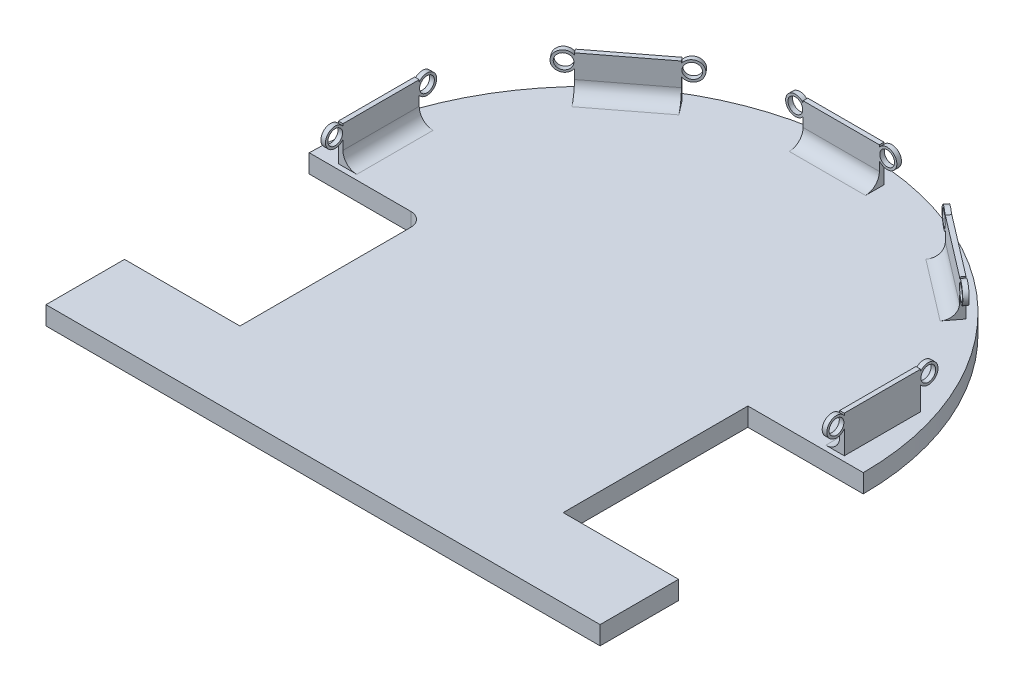
SolidWorks part; units mm, degrees
ref_plane "Front Plane" through (0, 0, 0) normal (0, 0, 1) x (1, 0, 0)
ref_plane "Top Plane" through (0, 0, 0) normal (0, 1, 0) x (1, 0, 0)
ref_plane "Right Plane" through (0, 0, 0) normal (1, 0, 0) x (0, 0, -1)
sketch "Sketch2" plane through (0, 0, 0) normal (0, 1, 0) x (1, 0, 0)
  line L0 (0, 0) -> (0, -17)
  line L1 (0, -17) -> (120, -17)
  line L2 (120, -17) -> (120, 0)
  line L3 (120, 0) -> (95, 0)
  line L4 (95, 0) -> (95, 40)
  line L5 (95, 40) -> (120, 40)
  line L6 (0, 0) -> (25, 0)
  line L7 (25, 0) -> (25, 40)
  line L8 (25, 40) -> (0, 40)
  arc A0 (0, 40) -> (120, 40) centre (60, 40) cw
  dimension "D1" = 120
  dimension "D2" = 25
  dimension "D3" = 25
  dimension "D4" = 25
  dimension "D5" = 25
  dimension "D6" = 40
  dimension "D7" = 40
  dimension "D15" = 17
extrude "Boss-Extrude1" add sketch "Sketch2" against normal blind 4
fillet "Fillet1" radius 3 1 edges at (25, -2, -40)
sketch "Sketch3" plane through (0, 0, 0) normal (0, 1, 0) x (1, 0, 0)
  line L0 (25, 37) -> (25, 0) construction
  line L1 (5.2129, 57.6133) -> (6.2129, 57.6133)
  line L2 (5.2129, 57.6133) -> (5.2129, 41.0933)
  line L3 (5.2129, 41.0933) -> (6.2129, 41.0933)
  line L4 (6.2129, 57.6133) -> (6.2129, 41.0933)
  line L5 (0, 40) -> (22, 40) construction
  dimension "D1" = 1
  dimension "D2" = 16.52
  dimension "D3" = 1.0933
  dimension "D4" = 18.7871
extrude "Boss-Extrude2" add sketch "Sketch3" along normal blind 8
sketch "Sketch4" plane through (5.2129, 0, 0) normal (-1, 0, 0) x (0, 0, 1)
  line L0 (-57.6133, 8) -> (-57.6133, 0) construction
  line L1 (-57.6133, 0) -> (-41.0933, 0) construction
  circle A0 centre (-59.2933, 6.3) radius 2.1
  dimension "D1" = 4.2
  dimension "D2" = 1.68
  dimension "D3" = 6.3
extrude "Boss-Extrude3" add sketch "Sketch4" against normal blind 1 contours A0
sketch "Sketch5" plane through (5.2129, 0, 0) normal (-1, 0, 0) x (0, 0, 1)
  circle A0 centre (-59.2933, 6.3) radius 1.6
  arc A1 (-57.6133, 7.56) -> (-57.6133, 5.04) centre (-59.2933, 6.3) ccw construction
  dimension "D1" = 3.2
  dimension "D2" = 0
extrude "Cut-Extrude1" cut sketch "Sketch5" against normal blind 1
sketch "Sketch6" plane through (5.2129, 0, 0) normal (-1, 0, 0) x (0, 0, 1)
  line L0 (-41.0933, 8) -> (-41.0933, 0) construction
  line L1 (-57.6133, 0) -> (-41.0933, 0) construction
  circle A0 centre (-39.4133, 6.3) radius 2.1
  dimension "D1" = 4.2
  dimension "D2" = 1.68
  dimension "D3" = 6.3
extrude "Boss-Extrude4" add sketch "Sketch6" against normal blind 1
sketch "Sketch7" plane through (5.2129, 0, 0) normal (-1, 0, 0) x (0, 0, 1)
  circle A0 centre (-39.4133, 6.3) radius 1.6
  arc A1 (-41.0933, 5.04) -> (-41.0933, 7.56) centre (-39.4133, 6.3) ccw construction
  dimension "D1" = 3.2
  dimension "D2" = 0
extrude "Cut-Extrude2" cut sketch "Sketch7" against normal blind 1
fillet "Fillet2" radius 3 1 edges at (6.2129, 0, -49.3533)
sketch "Sketch8" plane through (0, 0, 0) normal (0, 1, 0) x (1, 0, 0)
  line L0 (95, 40) -> (120, 40) construction
  line L1 (113.79, 57.61) -> (114.79, 57.61)
  line L2 (113.79, 57.61) -> (113.79, 41.09)
  line L3 (113.79, 41.09) -> (114.79, 41.09)
  line L4 (114.79, 57.61) -> (114.79, 41.09)
  line L5 (95, 0) -> (95, 40) construction
  dimension "D1" = 1
  dimension "D2" = 1.09
  dimension "D3" = 18.79
  dimension "D4" = 16.52
extrude "Boss-Extrude5" add sketch "Sketch8" along normal blind 8
fillet "Fillet3" radius 3 1 edges at (113.79, 0, -49.35)
sketch "Sketch9" plane through (114.79, 0, 0) normal (1, 0, 0) x (0, 0, -1)
  line L0 (41.09, 8) -> (41.09, 0) construction
  line L1 (100, 0) -> (40, 0) construction
  circle A0 centre (39.41, 6.3) radius 2.1
  dimension "D1" = 4.2
  dimension "D2" = 1.68
  dimension "D3" = 6.3
extrude "Boss-Extrude6" add sketch "Sketch9" against normal blind 1
sketch "Sketch10" plane through (114.79, 0, 0) normal (1, 0, 0) x (0, 0, -1)
  line L0 (57.61, 8) -> (57.61, 0) construction
  line L1 (100, 0) -> (40, 0) construction
  circle A0 centre (59.29, 6.3) radius 2.1
  dimension "D1" = 4.2
  dimension "D2" = 1.68
  dimension "D3" = 6.3
extrude "Boss-Extrude7" add sketch "Sketch10" against normal blind 1
sketch "Sketch11" plane through (114.79, 0, 0) normal (1, 0, 0) x (0, 0, -1)
  circle A0 centre (39.41, 6.3) radius 1.6
  circle A1 centre (59.29, 6.3) radius 1.6
  arc A2 (41.09, 7.56) -> (41.09, 5.04) centre (39.41, 6.3) ccw construction
  arc A3 (57.61, 5.04) -> (57.61, 7.56) centre (59.29, 6.3) ccw construction
  dimension "D1" = 3.2
  dimension "D3" = 3.2
  dimension "D2" = 0
  dimension "D4" = 0
extrude "Cut-Extrude3" cut sketch "Sketch11" against normal blind 1
sketch "Sketch13" plane through (0, 0, 0) normal (0, 1, 0) x (1, 0, 0)
  line L0 (95, 0) -> (95, 40) construction
  line L1 (68.26, 95.2232) -> (51.74, 95.2232)
  line L2 (68.26, 95.2232) -> (68.26, 96.2232)
  line L3 (68.26, 96.2232) -> (51.74, 96.2232)
  line L4 (51.74, 95.2232) -> (51.74, 96.2232)
  line L6 (25, 37) -> (25, 0) construction
  arc A0 (120, 40) -> (0, 40) centre (60, 40) ccw construction
  dimension "D1" = 1
  dimension "D2" = 16.52
  dimension "D3" = 26.74
  dimension "D4" = 55.2232
extrude "Boss-Extrude8" add sketch "Sketch13" along normal blind 8
sketch "Sketch14" plane through (0, 0, 0) normal (0, 1, 0) x (1, 0, 0)
  line L0 (102.3093, 79.9331) -> (89.1914, 89.9746)
  line L1 (88.5836, 89.1806) -> (101.7015, 79.1391)
  line L2 (101.7015, 79.1391) -> (102.3093, 79.9331)
  line L3 (89.1914, 89.9746) -> (88.5836, 89.1806)
  dimension "D1" = 1
  dimension "D2" = 16.52
extrude "Boss-Extrude9" add sketch "Sketch14" along normal blind 8
sketch "Sketch15" plane through (0, 0, 0) normal (0, 1, 0) x (1, 0, 0)
  line L0 (30.496, 90.2928) -> (17.3813, 80.2471)
  line L2 (17.9894, 79.4533) -> (31.1041, 89.4989)
  line L3 (31.1041, 89.4989) -> (30.496, 90.2928)
  line L4 (17.3813, 80.2471) -> (17.9894, 79.4533)
  line L6 (0, 40) -> (22, 40) construction
  arc A5 (120, 40) -> (0, 40) centre (60, 40) ccw construction
  point P9 (17.6853, 79.8502)
  dimension "D1" = 1
  dimension "D2" = 16.52
  dimension "D3" = 56.8669
  dimension "D4" = 52.549
extrude "Boss-Extrude10" add sketch "Sketch15" along normal blind 8
sketch "Sketch16" plane through (0, 0, -96.2232) normal (0, 0, -1) x (-1, 0, 0)
  line L0 (-68.26, 8) -> (-68.26, 0) construction
  line L1 (-68.26, 0) -> (-51.74, 0) construction
  circle A0 centre (-69.94, 6.3) radius 2.1
  dimension "D1" = 4.2
  dimension "D2" = 1.68
  dimension "D3" = 6.3
extrude "Boss-Extrude11" add sketch "Sketch16" against normal blind 1
sketch "Sketch17" plane through (0, 0, -96.2232) normal (0, 0, -1) x (-1, 0, 0)
  line L0 (-51.74, 8) -> (-51.74, 0) construction
  line L1 (-68.26, 0) -> (-51.74, 0) construction
  circle A0 centre (-50.06, 6.3) radius 2.1
  dimension "D1" = 4.2
  dimension "D3" = 6.3
  dimension "D2" = 1.68
extrude "Boss-Extrude12" add sketch "Sketch17" against normal blind 1
sketch "Sketch18" plane through (0, 0, -96.2232) normal (0, 0, -1) x (-1, 0, 0)
  circle A0 centre (-69.94, 6.3) radius 1.6
  arc A1 (-68.26, 7.56) -> (-68.26, 5.04) centre (-69.94, 6.3) ccw construction
  dimension "D1" = 3.2
  dimension "D2" = 0
extrude "Cut-Extrude4" cut sketch "Sketch18" against normal blind 1
sketch "Sketch19" plane through (0, 0, -96.2232) normal (0, 0, -1) x (-1, 0, 0)
  circle A0 centre (-50.06, 6.3) radius 1.6
  arc A1 (-51.74, 5.04) -> (-51.74, 7.56) centre (-50.06, 6.3) ccw construction
  dimension "D1" = 3.2
  dimension "D2" = 0
extrude "Cut-Extrude5" cut sketch "Sketch19" against normal blind 1
sketch "Sketch20" plane through (76.3806, 0, -99.7811) normal (0.6078, 0, -0.7941) x (-0.7941, 0, -0.6078)
  line L0 (-32.6533, 8) -> (-32.6533, 0) construction
  line L1 (-32.6533, 0) -> (-16.1333, 0) construction
  circle A0 centre (-34.3333, 6.3) radius 2.1
  dimension "D1" = 4.2
  dimension "D2" = 1.68
  dimension "D3" = 6.3
extrude "Boss-Extrude13" add sketch "Sketch20" against normal blind 1
sketch "Sketch21" plane through (76.3806, 0, -99.7811) normal (0.6078, 0, -0.7941) x (-0.7941, 0, -0.6078)
  line L0 (-16.1333, 8) -> (-16.1333, 0) construction
  line L1 (-32.6533, 0) -> (-16.1333, 0) construction
  circle A0 centre (-14.4533, 6.3) radius 2.1
  dimension "D1" = 4.2
  dimension "D2" = 1.68
  dimension "D3" = 6.3
extrude "Boss-Extrude14" add sketch "Sketch21" against normal blind 1
sketch "Sketch22" plane through (76.3806, 0, -99.7811) normal (0.6078, 0, -0.7941) x (-0.7941, 0, -0.6078)
  circle A0 centre (-34.3333, 6.3) radius 1.6
  circle A1 centre (-14.4533, 6.3) radius 1.6
  arc A2 (-32.6533, 7.56) -> (-32.6533, 5.04) centre (-34.3333, 6.3) ccw construction
  arc A3 (-16.1333, 5.04) -> (-16.1333, 7.56) centre (-14.4533, 6.3) ccw construction
  dimension "D1" = 3.2
  dimension "D2" = 0
  dimension "D3" = 3.2
  dimension "D4" = 0
extrude "Cut-Extrude6" cut sketch "Sketch22" against normal blind 1
sketch "Sketch23" plane through (-32.3116, 0, -42.1833) normal (-0.6081, 0, -0.7939) x (-0.7939, 0, 0.6081)
  line L0 (-79.1158, 8) -> (-79.1158, 0) construction
  line L1 (-79.1158, 0) -> (-62.5958, 0) construction
  circle A0 centre (-80.7958, 6.3) radius 2.1
  point P4 (-79.1158, 4)
  dimension "D1" = 4.2
  dimension "D3" = 6.3
  dimension "D2" = 1.68
extrude "Boss-Extrude15" add sketch "Sketch23" against normal blind 1
sketch "Sketch24" plane through (-32.3116, 0, -42.1833) normal (-0.6081, 0, -0.7939) x (-0.7939, 0, 0.6081)
  line L0 (-24.3236, 0) -> (-131.9557, 0) construction
  line L1 (-62.5958, 8) -> (-62.5958, 0) construction
  circle A0 centre (-60.9158, 6.3) radius 2.1
  dimension "D1" = 4.2
  dimension "D3" = 1.68
  dimension "D2" = 6.3
extrude "Boss-Extrude16" add sketch "Sketch24" against normal blind 1
sketch "Sketch25" plane through (-32.3116, 0, -42.1833) normal (-0.6081, 0, -0.7939) x (-0.7939, 0, 0.6081)
  circle A0 centre (-80.7958, 6.3) radius 1.6
  circle A1 centre (-60.9158, 6.2552) radius 1.6
  arc A2 (-79.1158, 7.56) -> (-79.1158, 5.04) centre (-80.7958, 6.3) ccw construction
  arc A3 (-62.5958, 5.04) -> (-62.5958, 7.56) centre (-60.9158, 6.3) ccw construction
  dimension "D1" = 3.2
  dimension "D2" = 3.2
  dimension "D3" = 0
  dimension "0" = 0
extrude "Cut-Extrude7" cut sketch "Sketch25" against normal blind 1
fillet "Fillet4" radius 3 3 edges at (95.1425, 0, -84.1598) (60, 0, -95.2232) (24.5467, 0, -84.4761)
